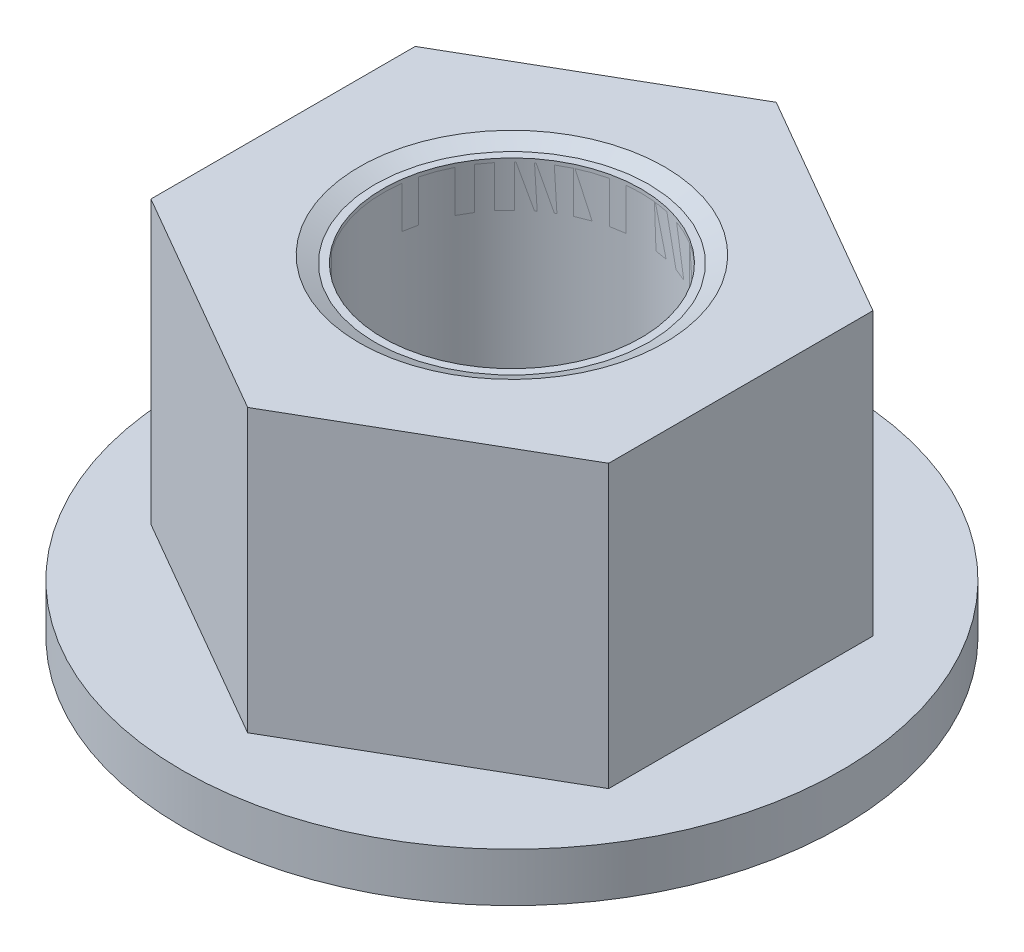
SolidWorks part; units mm, degrees
ref_plane "Front" through (0, 0, 0) normal (0, 0, 1) x (1, 0, 0)
ref_plane "Top" through (0, 0, 0) normal (0, 1, 0) x (1, 0, 0)
ref_plane "Right" through (0, 0, 0) normal (1, 0, 0) x (0, 0, -1)
sketch "Sketch1" plane through (0, 0, 0) normal (0, 1, 0) x (1, 0, 0)
  line L1 (0, 8.2489) -> (-7.1438, 4.1244)
  line L2 (-7.1438, 4.1244) -> (-7.1438, -4.1244)
  line L3 (-7.1438, -4.1244) -> (0, -8.2489)
  line L4 (0, -8.2489) -> (7.1437, -4.1244)
  line L5 (7.1437, -4.1244) -> (7.1437, 4.1244)
  line L6 (7.1437, 4.1244) -> (0, 8.2489)
  circle A0 centre (0, 0) radius 7.1438 construction
  dimension "Hex Flats" = 14.2875
extrude "Extrude1" add sketch "Sketch1" along normal blind 10.3187
sketch "Sketch8" plane through (0, 0, 0) normal (1, 0, 0) x (0, 0, -1)
  line L0 (0, 0) -> (10.287, 0)
  line L1 (10.287, 0) -> (10.287, 1.524)
  line L2 (10.287, 1.524) -> (0, 1.524)
  line L3 (0, 1.524) -> (0, 0)
  line L4 (0, 0) -> (0, -1.524) construction
  dimension "Flange Height" = 1.524
  dimension "Flange Dia" = 20.574
revolve "Revolve3" add sketch "Sketch8" angle 360 about L4
sketch "Sketch2" plane through (0, 0, 0) normal (1, 0, 0) x (0, 0, -1)
  line L0 (-4.7625, 0) -> (-4.7625, 10.3187) construction
  line L1 (0, 0) -> (4.7625, 0)
  line L2 (0, 0) -> (0, 10.3187)
  line L3 (0, 10.3187) -> (4.7625, 10.3187)
  line L4 (4.7625, 0) -> (4.7625, 10.3187)
  line L5 (-4.1244, 10.3187) -> (4.1244, 10.3187) construction
  line L7 (0, -4.7625) -> (0, 0) construction
  dimension "Thread Dia" = 9.525
revolve "Revolve1" [suppressed] add sketch "Sketch2" angle 360 about L7
sketch "Sketch3" plane through (0, 0, 0) normal (1, 0, 0) x (0, 0, -1)
  line L0 (4.7625, 10.3187) -> (-4.7625, 10.3187) construction
  line L1 (-4.7625, 10.3187) -> (-4.7625, 8.7312) construction
  line L2 (-4.7625, 8.7312) -> (4.7625, 10.3187) construction
  line L3 (4.7625, 10.3187) -> (4.7951, 10.123) construction
  line L4 (4.7951, 10.123) -> (5.0235, 8.7528)
  line L5 (5.0235, 8.7528) -> (4.0944, 9.1009)
  line L6 (4.0944, 9.1009) -> (4.0291, 9.4924)
  line L7 (4.0291, 9.4924) -> (4.7951, 10.123)
  line L8 (4.0617, 9.2967) -> (4.9093, 9.4379) construction
  line L9 (4.7625, 10.3187) -> (4.7625, 9.4135) construction
  line L10 (4.7625, 9.4135) -> (-4.7625, 7.826) construction
  line L11 (-4.7625, 7.826) -> (-4.7625, 8.7312) construction
  line L12 (-0.2832, 10.3187) -> (0.2832, 6.9207) construction
  line L13 (-4.7625, 0) -> (-4.7625, 10.3187) construction
  line L14 (0, 10.3187) -> (4.7625, 10.3187) construction
  line L15 (4.7625, 0) -> (4.7625, 10.3187) construction
  point P13 (0, 8.6197)
  dimension "D1" = 0.1984
  dimension "D2" = 0.3969
  dimension "Thread Pitch" = 1.5875
  dimension "D4" = 60
  dimension "D5" = 1.5875
revolve "Cut-Revolve1" [suppressed] cut sketch "Sketch3" angle 360 about L12
pattern_linear "LPattern1" [suppressed] count 7 spacing 1.5875 along (0, 1, 0) count 2 spacing 1.5875 along (0, 1, 0)
sketch "Sketch4" plane through (0, 0, 0) normal (1, 0, 0) x (0, 0, -1)
  line L0 (0, 10.3187) -> (4.7625, 10.3187)
  line L1 (4.7625, 10.3187) -> (4.0291, 9.9768)
  line L2 (4.0291, 9.9768) -> (4.0291, 0.342)
  line L3 (4.0291, 0.342) -> (4.7625, 0)
  line L4 (4.7625, 0) -> (0, 0)
  line L5 (0, 0) -> (0, 10.3187)
  line L6 (4.7625, 0) -> (4.7625, 10.3187) construction
  line L7 (0, 10.3187) -> (4.7625, 10.3187) construction
  line L8 (0, 0) -> (4.7625, 0) construction
  line L9 (0, 0) -> (0, 10.3187) construction
  line L10 (0, 10.3187) -> (0, 11.128) construction
  dimension "D1" = 25
revolve "Cut-Revolve2" cut sketch "Sketch4" angle 360 about L10
combine bodies "Combine1" [suppressed] operation type subtract main body 112 bodies to subtract 111
sketch "Sketch5" plane through (0, 0, 0) normal (1, 0, 0) x (0, 0, -1)
  line L0 (10.287, 1.524) -> (0, 1.524) construction
  line L1 (0, 0) -> (10.287, 0) construction
  line L2 (8.2489, 1.524) -> (8.2489, 8.0836)
  line L3 (8.2489, 8.0836) -> (7.1438, 8.599)
  line L4 (5.424, 10.3187) -> (5.424, 11.5887)
  line L5 (5.424, 11.5887) -> (9.5189, 11.5887)
  line L6 (9.5189, 11.5887) -> (9.5189, 1.524)
  line L9 (7.1438, 8.599) -> (7.1438, 0) construction
  line L13 (8.2489, 1.524) -> (9.5189, 1.524)
  line L15 (0, 0) -> (0, 11.5887) construction
  line L20 (0, 11.5887) -> (5.424, 11.5887) construction
  line L22 (0, 10.3187) -> (4.7625, 10.3187) construction
  arc A0 (7.1438, 8.599) -> (5.424, 10.3187) centre (5.424, 8.599) ccw
  dimension "D4" = 1.7198
  dimension "D1" = 1.27
  dimension "D2" = 115
  dimension "D3" = 10.3187
revolve "Cut-Revolve3" [suppressed] cut sketch "Sketch5" angle 360 about L15
sketch "Sketch6" plane through (0, 0, 0) normal (1, 0, 0) x (0, 0, -1)
  line L0 (0, 8.599) -> (6.9914, 8.599)
  line L1 (5.424, 10.1663) -> (4.7265, 10.1663)
  line L2 (0, 11.5887) -> (0, 8.599)
  line L3 (4.7265, 11.5887) -> (0, 11.5887)
  line L4 (0, 11.5887) -> (5.424, 11.5887) construction
  line L5 (0, 0) -> (0, 11.5887) construction
  line L6 (0, 11.5887) -> (0, 44.323) construction
  line L7 (4.7265, 10.1663) -> (4.7265, 11.5887)
  line L8 (5.424, 10.3187) -> (5.424, 10.1663) construction
  line L9 (4.7265, 10.1663) -> (4.0291, 10.1663) construction
  line L10 (4.0291, 10.1663) -> (4.0291, 9.9768) construction
  arc A0 (6.9914, 8.599) -> (5.424, 10.1663) centre (5.424, 8.599) ccw
  arc A1 (7.1438, 8.599) -> (5.424, 10.3187) centre (5.424, 8.599) ccw construction
  dimension "D1" = 0.1524
revolve "Cut-Revolve4" [suppressed] cut sketch "Sketch6" angle 360 about L6
sketch "Sketch7" plane through (0, 0, 0) normal (1, 0, 0) x (0, 0, -1)
  line L0 (4.0291, 8.6752) -> (6.9132, 8.6752)
  line L1 (5.424, 10.0901) -> (4.0291, 10.0901)
  line L2 (4.0291, 10.0901) -> (4.0291, 8.6752)
  line L3 (4.0291, 8.6752) -> (0, 8.6752) construction
  line L4 (0, 8.6752) -> (0, 10.0901) construction
  line L5 (0, 10.0901) -> (4.0291, 10.0901) construction
  line L6 (4.0291, 8.6752) -> (4.0291, 8.599) construction
  line L7 (0, 8.599) -> (6.9914, 8.599) construction
  line L8 (5.424, 10.0901) -> (5.424, 10.1663) construction
  arc A0 (6.9132, 8.6752) -> (5.424, 10.0901) centre (5.424, 8.599) ccw
  arc A2 (6.9914, 8.599) -> (5.424, 10.1663) centre (5.424, 8.599) ccw construction
  dimension "D1" = 0.0762
revolve "Revolve2" add sketch "Sketch7" angle 360 about L4
equation "\"D1@Sketch3\"=\"Thread Pitch@Sketch3\"/8"
equation "\"D2@Sketch3\"=\"Thread Pitch@Sketch3\"/4"
equation "\"D5@Sketch3\"=\"Thread Pitch@Sketch3\""
equation "\"D4@LPattern1\"=\"Thread Pitch@Sketch3\""
equation "\"D3@LPattern1\"=\"Thread Pitch@Sketch3\""
equation "\"D1@LPattern1\"=\"Height@Extrude1\"/\"Thread Pitch@Sketch3\""
equation "\"D4@Sketch5\"=\"Height@Extrude1\"/6"
